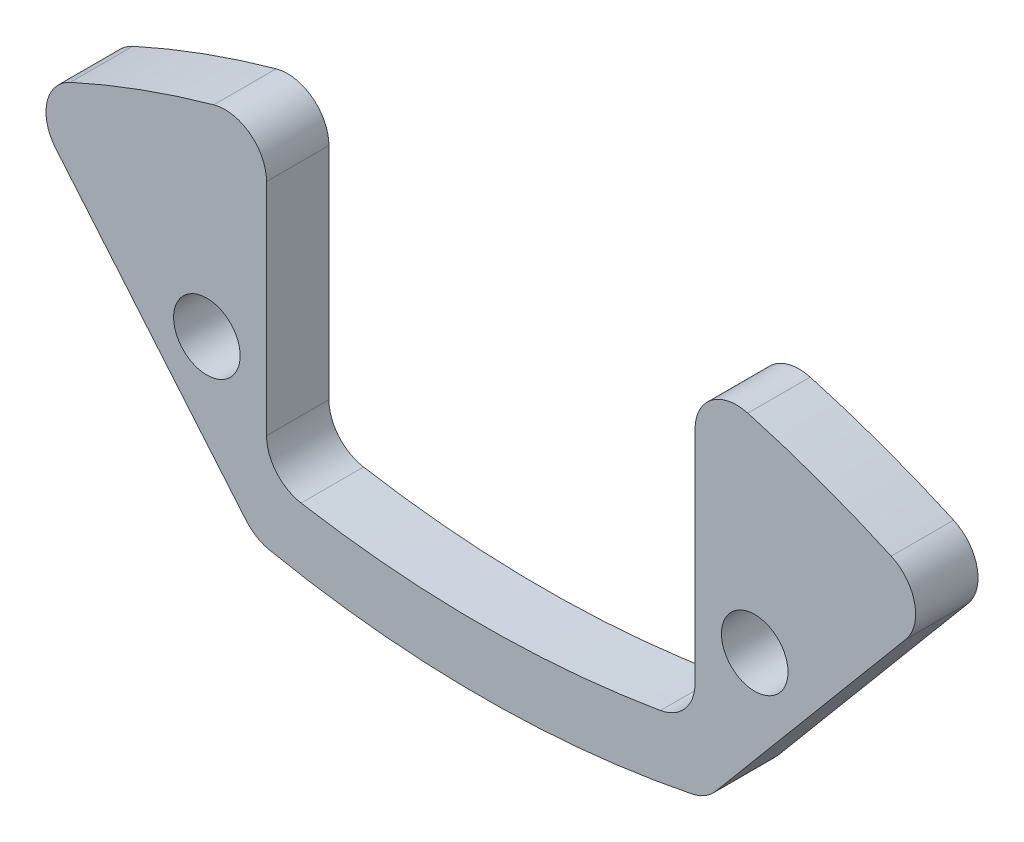
SolidWorks part; units mm, degrees
material "ﾎﾟﾘｶｰﾎﾞﾈｰﾄ(PC)高粘度"
ref_plane "正面" through (0, 0, 0) normal (0, 0, 1) x (1, 0, 0)
ref_plane "平面" through (0, 0, 0) normal (0, 1, 0) x (1, 0, 0)
ref_plane "右側面" through (0, 0, 0) normal (1, 0, 0) x (0, 0, -1)
sketch "ｽｹｯﾁ1" plane through (0, 0, 0) normal (0, 0, 1) x (1, 0, 0)
  circle A0 centre (0, 0) radius 47.75
  dimension "D1" = 95.5
extrude "ﾎﾞｽ - 押し出し1" add sketch "ｽｹｯﾁ1" along normal blind 3
sketch "ｽｹｯﾁ2" plane through (0, 0, 3) normal (0, 0, 1) x (1, 0, 0)
  line L0 (-10.3, 46.6259) -> (-10.3, 31.8257)
  line L1 (10.3, 46.6259) -> (10.3, 31.8257)
  line L2 (0, 47.75) -> (0, -47.75) construction
  line L8 (0, 0) -> (-16.3315, 44.8703) construction
  line L9 (0, 0) -> (16.3315, 44.8703) construction
  line L13 (0, 30.78) -> (0, 41.18) construction
  line L94 (-10.3, 31.8257) -> (-12.5669, 31.0006) construction
  line L95 (10.3, 31.8257) -> (12.5669, 31.0006) construction
  line L96 (-22.0803, 42.3382) -> (-10.8369, 28.9388)
  line L97 (22.0803, 42.3382) -> (10.8369, 28.9388)
  circle A0 centre (0, 0) radius 47.75 construction
  arc A1 (-10.3, 46.6259) -> (10.3, 46.6259) centre (0, 0) cw
  arc A2 (-10.3, 31.8257) -> (10.3, 31.8257) centre (0, 82.03) ccw
  arc A19 (-10.8369, 28.9388) -> (10.8369, 28.9388) centre (0, 79.03) ccw
  arc A20 (-22.0803, 42.3382) -> (22.0803, 42.3382) centre (0, 0) ccw
  circle A21 centre (-13.1678, 36.1782) radius 1.6
  circle A22 centre (13.1678, 36.1782) radius 1.6
  point P6 (-11.4335, 31.4131)
  point P11 (0, 41.18)
  point P16 (11.4335, 31.4131)
  point P139 (0, 0)
  dimension "D2" = 20.6
  dimension "D7" = 51.25
  dimension "D10" = 3
  dimension "D11" = 38.5
  dimension "D12" = 38.5
  dimension "D13" = 3.2
  dimension "D1" = 41.18
  dimension "D3" = 10.3
  dimension "D4" = 20
  dimension "D5" = 40
  dimension "D6" = 10.4
  dimension "D8" = 40
  dimension "D9" = 40
extrude "ｶｯﾄ - 押し出し1" cut sketch "ｽｹｯﾁ2" against normal through all
fillet "ﾌｨﾚｯﾄ1" radius 2 8 edges at (-10.3, 46.6259, 1.5) (-22.0803, 42.3382, 1.5) (22.0803, 42.3382, 1.5) (10.3, 46.6259, 1.5) (10.8369, 28.9388, 1.5) (-10.8369, 28.9388, 1.5) (10.3, 31.8257, 1.5) (-10.3, 31.8257, 1.5)
